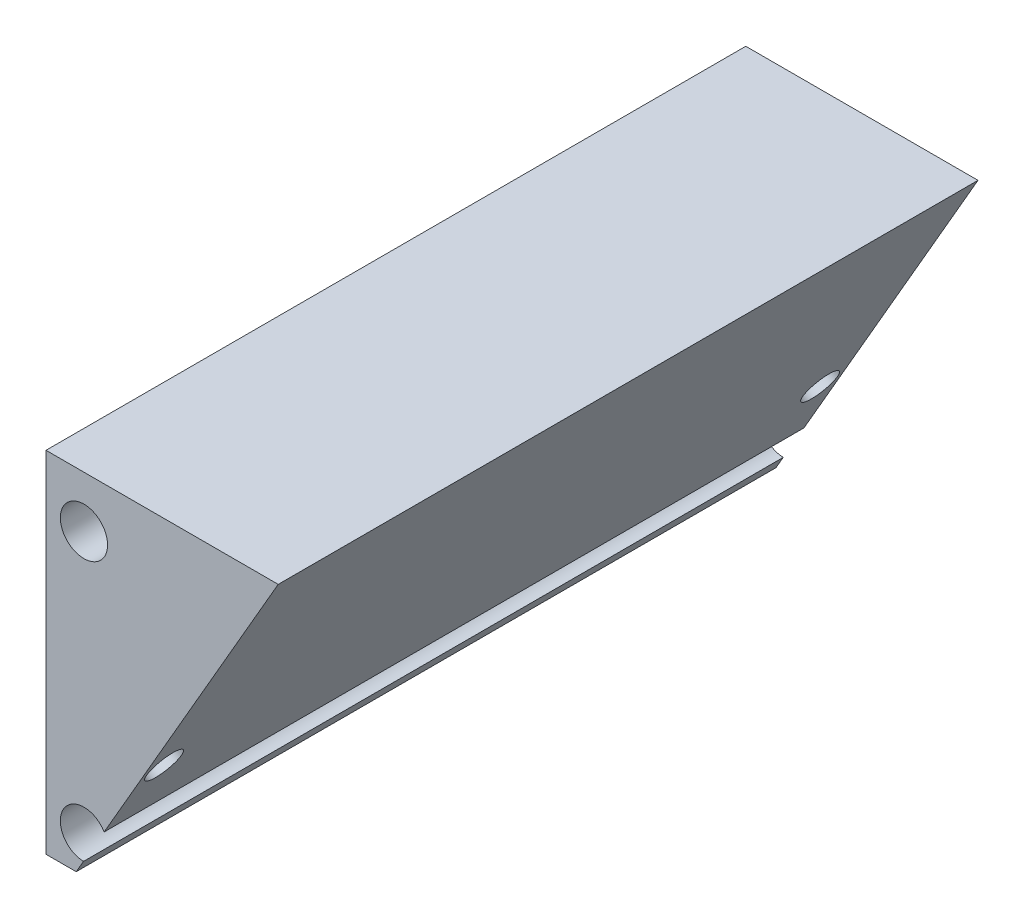
SolidWorks part; units mm, degrees
ref_plane "Front" through (0, 0, 0) normal (0, 0, 1) x (1, 0, 0)
ref_plane "Top" through (0, 0, 0) normal (0, 1, 0) x (1, 0, 0)
ref_plane "Right" through (0, 0, 0) normal (1, 0, 0) x (0, 0, -1)
sketch "草图1" plane through (0, 0, 0) normal (0, 0, 1) x (1, 0, 0)
  line L0 (0, 0) -> (5.7735, 10)
  line L1 (-7.5, 10) -> (5.7735, 10)
  line L2 (-7.5, 10) -> (-7.5, -10)
  line L3 (-7.5, -10) -> (-5.7735, -10)
  line L4 (-5.3572, -9.279) -> (-5.7735, -10)
  line L5 (-7.5, 10) -> (0, 0) construction
  line L6 (-7.5, -10) -> (0, 0) construction
  line L7 (0, 0) -> (-4.1749, -7.2312)
  circle A1 centre (-5.3304, 7.0708) radius 1.35
  arc A2 (-4.1749, -7.2312) -> (-5.3572, -9.279) centre (-5.3304, -7.9292) ccw
  point P0 (0, 0)
extrude "凸台-拉伸1" add sketch "草图1" along normal blind 40
sketch "草图2" plane through (0, 0, 0) normal (0.866, -0.5, 0) x (0, 0, -1)
  circle A1 centre (-1.25, -4) radius 1
  circle A2 centre (-38.75, -4) radius 1
extrude "切除-拉伸1" cut sketch "草图2" against normal blind 40
